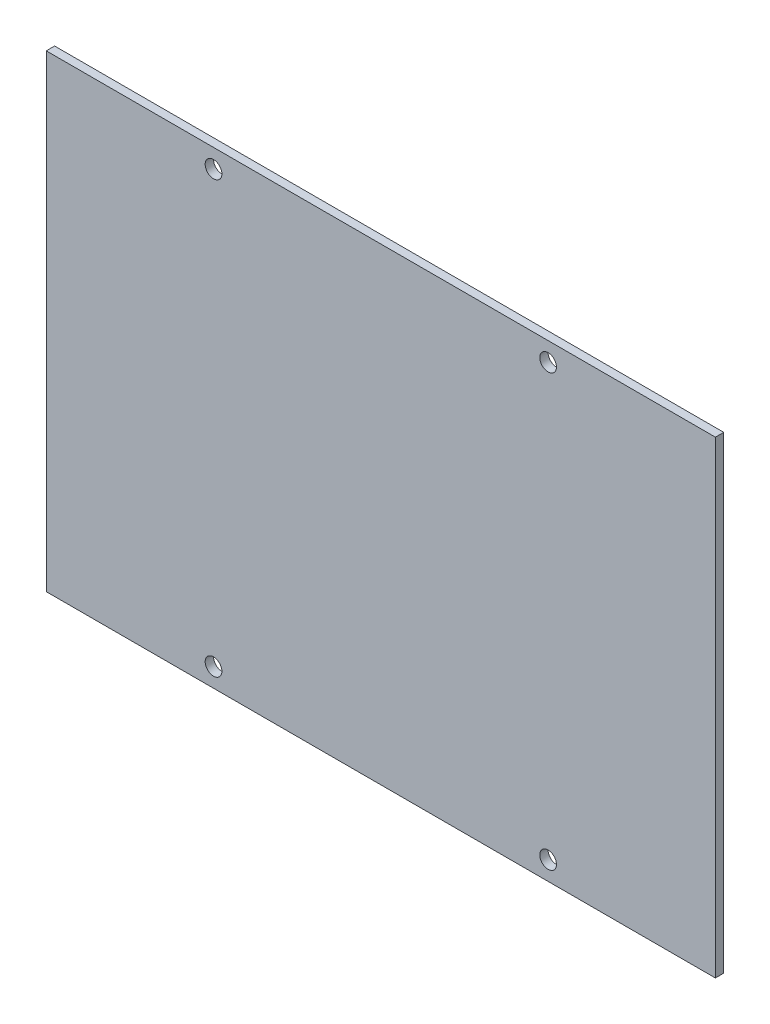
SolidWorks part; units mm, degrees
ref_plane "Ön Düzlem" through (0, 0, 0) normal (0, 0, 1) x (1, 0, 0)
ref_plane "Üst Düzlem" through (0, 0, 0) normal (0, 1, 0) x (1, 0, 0)
ref_plane "Sağ Düzlem" through (0, 0, 0) normal (1, 0, 0) x (0, 0, -1)
sketch "Sketch1" plane through (0, 0, 0) normal (0, 0, 1) x (1, 0, 0)
  line L1 (0, 0) -> (160, 0)
  line L2 (0, 0) -> (0, 112)
  line L3 (0, 112) -> (160, 112)
  line L4 (160, 0) -> (160, 112)
extrude "Boss-Extrude1" add sketch "Sketch1" along normal blind 2
sketch "Sketch2" plane through (0, 0, 2) normal (0, 0, 1) x (1, 0, 0)
  line L0 (0, 112) -> (0, 0) construction
  line L1 (160, 112) -> (0, 112) construction
  line L2 (160, 0) -> (160, 112) construction
  line L3 (0, 0) -> (160, 0) construction
  circle A0 centre (40, 107.5) radius 2
  circle A1 centre (120, 107.5) radius 2
  circle A2 centre (40, 4.5) radius 2
  circle A3 centre (120, 4.5) radius 2
  dimension "D1" = 40
  dimension "D3" = 40
  dimension "D4" = 4.5
  dimension "D5" = 40
  dimension "D7" = 40
  dimension "D2" = 4.5
  dimension "D6" = 4.5
  dimension "D8" = 4.5
extrude "Cut-Extrude1" cut sketch "Sketch2" against normal through all
